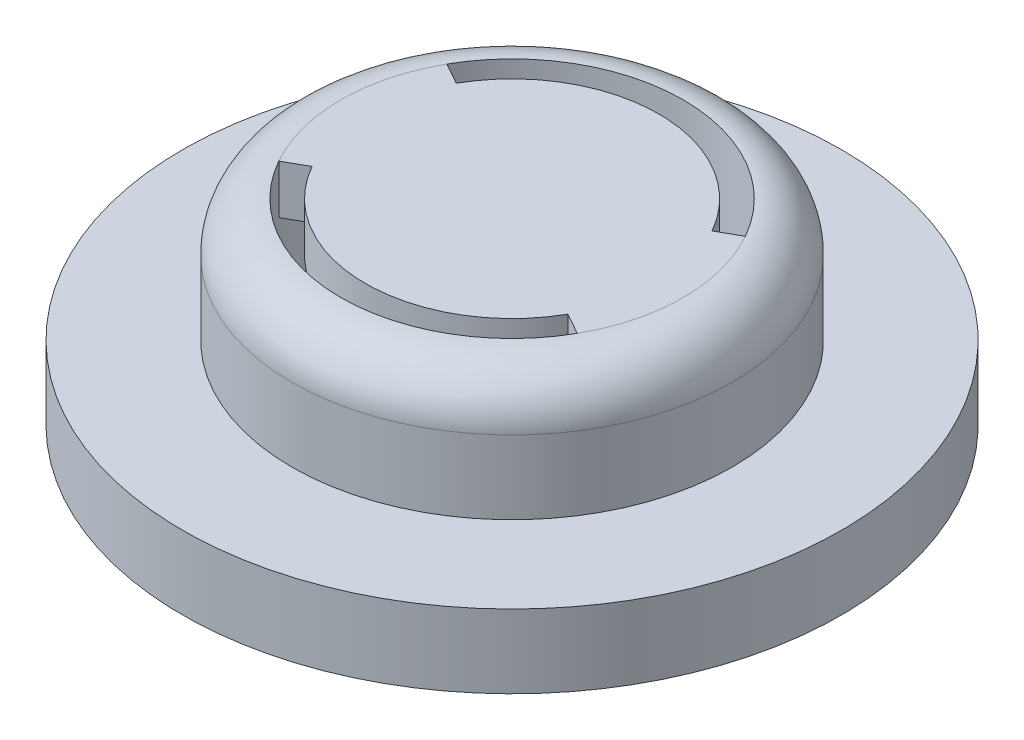
SolidWorks part; units mm, degrees
ref_plane "Front Plane" through (0, 0, 0) normal (0, 0, 1) x (1, 0, 0)
ref_plane "Top Plane" through (0, 0, 0) normal (0, 1, 0) x (1, 0, 0)
ref_plane "Right Plane" through (0, 0, 0) normal (1, 0, 0) x (0, 0, -1)
sketch "Sketch1" plane through (0, 0, 0) normal (0, 1, 0) x (1, 0, 0)
  circle A0 centre (0, 0) radius 9
  dimension "D1" = 18
extrude "Boss-Extrude1" add sketch "Sketch1" along normal blind 5 contours A0
sketch "Sketch2" plane through (0, 0, 0) normal (0, -1, 0) x (1, 0, 0)
  circle A0 centre (0, 0) radius 13.469
extrude "Boss-Extrude2" add sketch "Sketch2" along normal blind 3
shell "Shell1" thickness 2
fillet "Fillet1" radius 2 1 edges at (0, 5, 9)
sketch "Sketch3" plane through (0, 5, 0) normal (0, 1, 0) x (1, 0, 0)
  line L0 (5.2276, -2.9448) -> (6.0989, -3.4356)
  line L1 (5.2276, 2.9448) -> (6.0989, 3.4356)
  line L2 (0, 7) -> (0, -7) construction
  line L3 (-5.2276, -2.9448) -> (-6.0989, -3.4356)
  line L4 (-5.2276, 2.9448) -> (-6.0989, 3.4356)
  arc A0 (6.0989, 3.4356) -> (-6.0989, 3.4356) centre (0, 0) ccw
  arc A1 (5.2276, 2.9448) -> (-5.2276, 2.9448) centre (0, 0) ccw
  circle A2 centre (0, 0) radius 6 construction
  circle A3 centre (0, 0) radius 7 construction
  arc A4 (-5.2276, -2.9448) -> (5.2276, -2.9448) centre (0, 0) ccw
  arc A5 (-6.0989, -3.4356) -> (6.0989, -3.4356) centre (0, 0) ccw
  dimension "D1" = 1
extrude "Cut-Extrude1" cut sketch "Sketch3" against normal blind 13
equation "\"0.0c2m\"=0.3"
